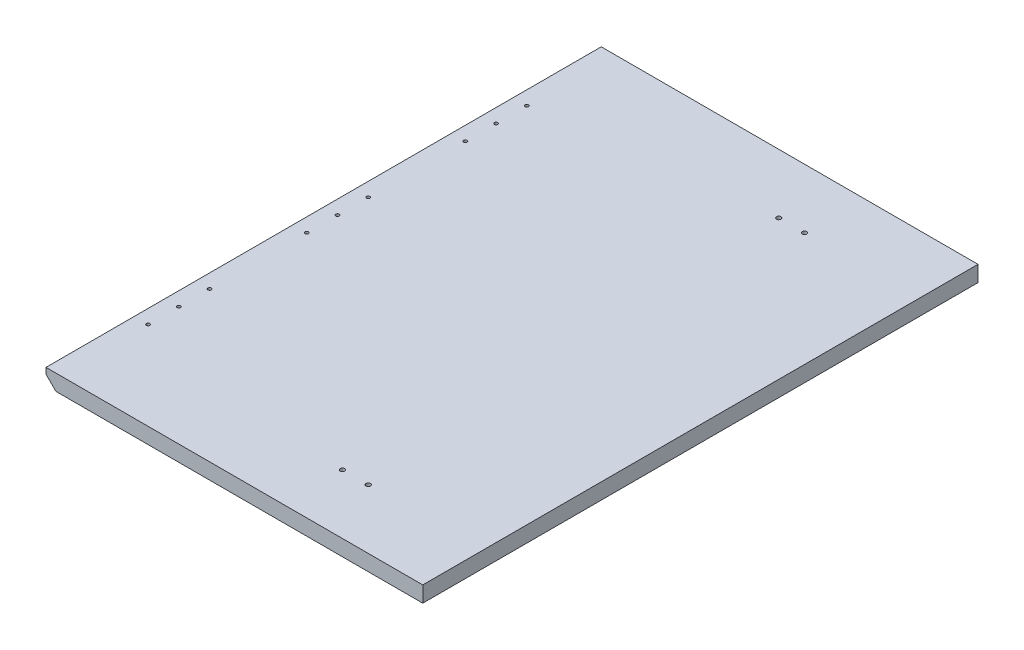
SolidWorks part; units mm, degrees
ref_plane "Front Plane" through (0, 0, 0) normal (0, 0, 1) x (1, 0, 0)
ref_plane "Top Plane" through (0, 0, 0) normal (0, 1, 0) x (1, 0, 0)
ref_plane "Right Plane" through (0, 0, 0) normal (1, 0, 0) x (0, 0, -1)
other "Bounding Box"
ref_plane "Default Plane" through (-190, 0, -280) normal (1, 0, 0) x (0, 0, -1)
sketch "Sketch1" plane through (0, 0, 0) normal (0, 1, 0) x (1, 0, 0)
  line L1 (-190, -280) -> (190, -280)
  line L2 (-190, -280) -> (-190, 280)
  line L3 (-190, 280) -> (190, 280)
  line L4 (190, -280) -> (190, 280)
  line L5 (-190, -280) -> (190, 280) construction
  line L6 (-190, 280) -> (190, -280) construction
  point P0 (0, 0)
  dimension "D1" = 380
  dimension "D2" = 560
extrude "Boss-Extrude1" add sketch "Sketch1" along normal blind 16
sketch "Sketch2" plane through (0, 0, 0) normal (0, -1, 0) x (1, 0, 0)
  line L0 (-190, -280) -> (-190, 280) construction
  line L1 (-190, 117.5) -> (-160, 117.5)
  line L2 (-190, 117.5) -> (-190, 202.5)
  line L3 (-190, 202.5) -> (-160, 202.5)
  line L4 (-160, 117.5) -> (-160, 202.5)
  line L5 (-190, 280) -> (190, 280) construction
  line L6 (0, 0) -> (-160, 0) construction
  line L11 (-190, -42.5) -> (-160, -42.5)
  line L12 (-190, -42.5) -> (-190, 42.5)
  line L13 (-190, 42.5) -> (-160, 42.5)
  line L14 (-160, -42.5) -> (-160, 42.5)
  line L15 (-190, -202.5) -> (-160, -202.5)
  line L16 (-190, -202.5) -> (-190, -117.5)
  line L17 (-190, -117.5) -> (-160, -117.5)
  line L18 (-160, -202.5) -> (-160, -117.5)
  line L19 (190, -280) -> (-190, -280) construction
  point P6 (-160, 160)
  point P24 (-160, 0)
  dimension "D1" = 30
  dimension "D2" = 85
  dimension "D3" = 120
  dimension "D4" = 3
  dimension "D5" = 77.5
extrude "Cut-Extrude1" cut sketch "Sketch2" against normal blind 10
sketch "Sketch3" plane through (0, 16, 0) normal (0, 1, 0) x (1, 0, 0)
  line L4 (190, 280) -> (-190, 280) construction
  line L5 (-190, -280) -> (-150, -280)
  line L6 (-190, -280) -> (-190, 280)
  line L7 (-190, 280) -> (-150, 280)
  line L12 (-150, -280) -> (-150, 280)
  dimension "D1" = 40
extrude "Boss-Extrude4" [suppressed] add sketch "Sketch3" along normal blind 16
chamfer "Chamfer2" distance 10 angle 45 4 edges at (-190, 0, 241.25) (-190, 0, 80) (-190, 0, -80) (-190, 0, -241.25)
hole_wizard "#8-36 Tapped Hole1" positions "Sketch6" profile "Sketch5" tap size "#8-36" standard "ANSI Inch"
sketch "Sketch6" plane through (0, 10, 0) normal (0, -1, 0) x (-1, 0, 0)
  line L2 (176, -160) -> (218.3401, -160) construction
  line L4 (190, -117.5) -> (160, -117.5) construction
  line L5 (160, -202.5) -> (190, -202.5) construction
  line L7 (160, -117.5) -> (160, -202.5) construction
  point P0 (176, -191)
  point P2 (176, -160)
  point P4 (176, -129)
  dimension "D1" = 62
  dimension "D2" = 16
sketch "Sketch5" plane through (-176, 10, 191) normal (1, 0, 0) x (0, 0, -1)
  line L0 (0, 0) -> (0, 26.0378)
  line L1 (0, 26.0378) -> (1.7272, 25)
  line L2 (1.7272, 25) -> (1.7272, 0)
  line L5 (1.7272, 0) -> (0, 0)
  line L10 (0, 26.0378) -> (-1.7272, 25) construction
  line L11 (0, -6.35) -> (0, 107.95) construction
  dimension "Tap Drill Dia." = 3.4544
  dimension "Tap Drill Depth" = 25
  dimension "Drill Angle" = 118
cosmetic thread "Hole Thread1" parameters "D1"=20, "D2"=4.1656
cosmetic thread "Hole Thread2" parameters "D1"=20, "D2"=4.1656
cosmetic thread "Hole Thread3" parameters "D1"=20, "D2"=4.1656
pattern_linear "LPattern1" count 3 spacing 160 along (0, 0, -1) of "#8-36 Tapped Hole1"
cosmetic thread "Hole Thread4" parameters "D1"=20, "D2"=4.1656
cosmetic thread "Hole Thread5" parameters "D1"=20, "D2"=4.1656
cosmetic thread "Hole Thread6" parameters "D1"=20, "D2"=4.1656
cosmetic thread "Hole Thread7" parameters "D1"=20, "D2"=4.1656
cosmetic thread "Hole Thread8" parameters "D1"=20, "D2"=4.1656
cosmetic thread "Hole Thread9" parameters "D1"=20, "D2"=4.1656
hole_wizard "CSK for #8 Flat Head Machine Screw (100)1" positions "Sketch9" profile "Sketch8" countersink size "#8" standard "ANSI Inch"
sketch "Sketch9" plane through (0, 0, 0) normal (0, -1, 0) x (-1, 0, 0)
  line L0 (-190, -280) -> (-190, 280) construction
  line L1 (180, -280) -> (-190, -280) construction
  point P0 (-75, -220)
  point P2 (-49, -220)
  dimension "D1" = 115
  dimension "D2" = 26
  dimension "D3" = 60
sketch "Sketch8" plane through (75, 0, 220) normal (1, 0, 0) x (0, 0, -1)
  line L0 (0, 0) -> (0, 26.3507)
  line L1 (0, 26.3507) -> (2.2479, 25)
  line L2 (2.2479, 25) -> (2.2479, 1.6518)
  line L3 (2.2479, 1.6518) -> (4.2164, 0)
  line L5 (4.2164, 0) -> (0, 0)
  line L6 (-2.2479, 1.6518) -> (-4.2164, 0) construction
  line L10 (0, 26.3507) -> (-2.2479, 25) construction
  line L11 (0, -6.35) -> (0, 107.95) construction
  dimension "Hole Dia." = 4.4958
  dimension "Hole Depth" = 25
  dimension "Near C'Sink Dia." = 8.4328
  dimension "Near C'Sink Angle" = 100
  dimension "Drill Angle" = 118
mirror "Mirror1" about plane through (0, 0, 0) normal (0, 0, 1) of "CSK for #8 Flat Head Machine Screw (100)1"
